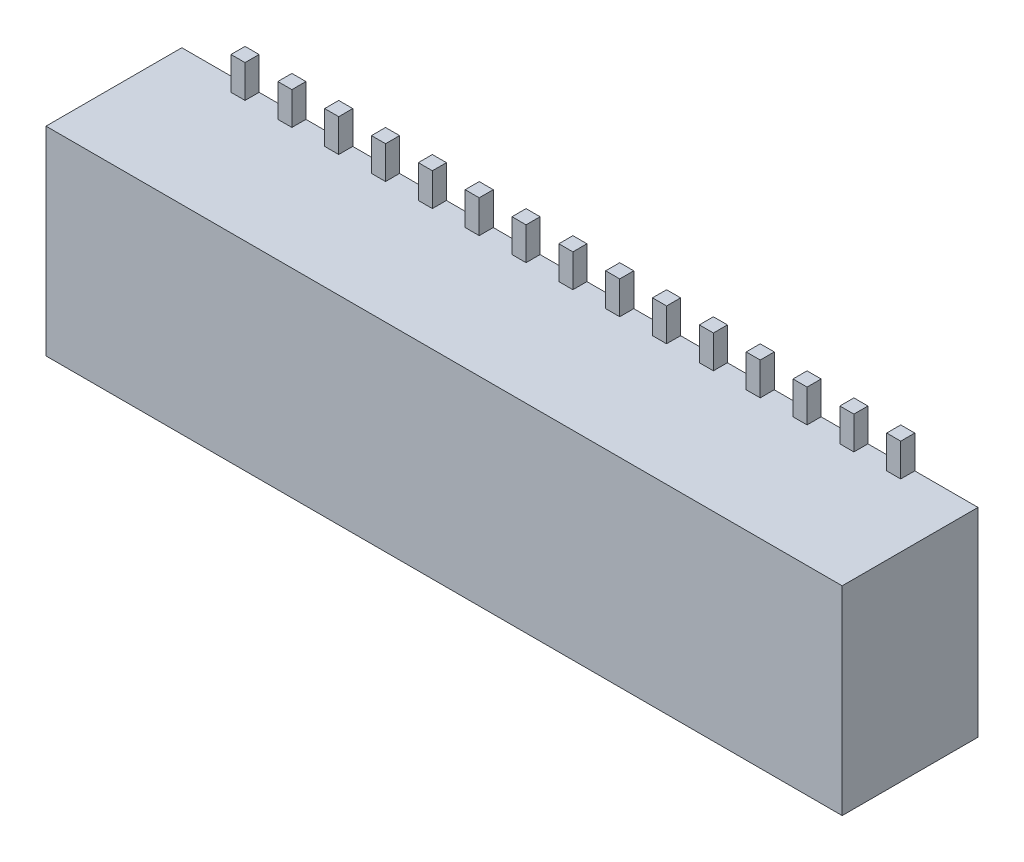
SolidWorks part; units mm, degrees
ref_plane "Front Plane" through (0, 0, 0) normal (0, 0, 1) x (1, 0, 0)
ref_plane "Top Plane" through (0, 0, 0) normal (0, 1, 0) x (1, 0, 0)
ref_plane "Right Plane" through (0, 0, 0) normal (1, 0, 0) x (0, 0, -1)
sketch "Sketch1" plane through (0, 0, 0) normal (0, 0, 1) x (1, 0, 0)
  line L1 (-8.5, 2.125) -> (8.5, 2.125)
  line L2 (-8.5, 2.125) -> (-8.5, -2.125)
  line L3 (-8.5, -2.125) -> (8.5, -2.125)
  line L4 (8.5, 2.125) -> (8.5, -2.125)
  line L5 (-8.5, 2.125) -> (8.5, -2.125) construction
  line L6 (-8.5, -2.125) -> (8.5, 2.125) construction
  point P0 (0, 0)
  dimension "D1" = 17
  dimension "D2" = 4.25
extrude "Boss-Extrude1" add sketch "Sketch1" along normal blind 2.9
sketch "Sketch2" plane through (0, -2.125, 0) normal (0, -1, 0) x (1, 0, 0)
  line L0 (-8.5, 0) -> (8.5, 0) construction
  line L1 (-7.7, 2.4) -> (7.7, 2.4)
  line L2 (-7.7, 2.4) -> (-7.7, 0.5)
  line L3 (-7.7, 0.5) -> (7.7, 0.5)
  line L4 (7.7, 2.4) -> (7.7, 0.5)
  line L5 (-8.5, 2.9) -> (8.5, 2.9) construction
  line L6 (-8.5, 2.9) -> (-8.5, 0) construction
  line L7 (8.5, 2.9) -> (8.5, 0) construction
  dimension "D1" = 0.5
  dimension "D2" = 0.5
  dimension "D3" = 0.8
  dimension "D4" = 0.8
extrude "Cut-Extrude1" cut sketch "Sketch2" against normal blind 2.9
sketch "Sketch3" plane through (0, 0.775, 0) normal (0, -1, 0) x (1, 0, 0)
  line L0 (-7.7, 1.45) -> (-7.15, 1.45) construction
  line L1 (-7.15, 1.75) -> (-6.85, 1.75)
  line L2 (-7.15, 1.75) -> (-7.15, 1.15)
  line L3 (-7.15, 1.15) -> (-6.85, 1.15)
  line L4 (-6.85, 1.75) -> (-6.85, 1.15)
  line L5 (-7.7, 2.4) -> (-7.7, 0.5) construction
  line L6 (-5.85, 1.75) -> (-5.85, 1.15)
  line L7 (-6.15, 1.15) -> (-5.85, 1.15)
  line L8 (-6.15, 1.75) -> (-6.15, 1.15)
  line L9 (-6.15, 1.75) -> (-5.85, 1.75)
  line L10 (-4.85, 1.75) -> (-4.85, 1.15)
  line L11 (-5.15, 1.15) -> (-4.85, 1.15)
  line L12 (-5.15, 1.75) -> (-5.15, 1.15)
  line L13 (-5.15, 1.75) -> (-4.85, 1.75)
  line L14 (-3.85, 1.75) -> (-3.85, 1.15)
  line L15 (-4.15, 1.15) -> (-3.85, 1.15)
  line L16 (-4.15, 1.75) -> (-4.15, 1.15)
  line L17 (-4.15, 1.75) -> (-3.85, 1.75)
  line L18 (-2.85, 1.75) -> (-2.85, 1.15)
  line L19 (-3.15, 1.15) -> (-2.85, 1.15)
  line L20 (-3.15, 1.75) -> (-3.15, 1.15)
  line L21 (-3.15, 1.75) -> (-2.85, 1.75)
  line L22 (-1.85, 1.75) -> (-1.85, 1.15)
  line L23 (-2.15, 1.15) -> (-1.85, 1.15)
  line L24 (-2.15, 1.75) -> (-2.15, 1.15)
  line L25 (-2.15, 1.75) -> (-1.85, 1.75)
  line L26 (-0.85, 1.75) -> (-0.85, 1.15)
  line L27 (-1.15, 1.15) -> (-0.85, 1.15)
  line L28 (-1.15, 1.75) -> (-1.15, 1.15)
  line L29 (-1.15, 1.75) -> (-0.85, 1.75)
  line L30 (0.15, 1.75) -> (0.15, 1.15)
  line L31 (-0.15, 1.15) -> (0.15, 1.15)
  line L32 (-0.15, 1.75) -> (-0.15, 1.15)
  line L33 (-0.15, 1.75) -> (0.15, 1.75)
  line L34 (1.15, 1.75) -> (1.15, 1.15)
  line L35 (0.85, 1.15) -> (1.15, 1.15)
  line L36 (0.85, 1.75) -> (0.85, 1.15)
  line L37 (0.85, 1.75) -> (1.15, 1.75)
  line L38 (2.15, 1.75) -> (2.15, 1.15)
  line L39 (1.85, 1.15) -> (2.15, 1.15)
  line L40 (1.85, 1.75) -> (1.85, 1.15)
  line L41 (1.85, 1.75) -> (2.15, 1.75)
  line L42 (3.15, 1.75) -> (3.15, 1.15)
  line L43 (2.85, 1.15) -> (3.15, 1.15)
  line L44 (2.85, 1.75) -> (2.85, 1.15)
  line L45 (2.85, 1.75) -> (3.15, 1.75)
  line L46 (4.15, 1.75) -> (4.15, 1.15)
  line L47 (3.85, 1.15) -> (4.15, 1.15)
  line L48 (3.85, 1.75) -> (3.85, 1.15)
  line L49 (3.85, 1.75) -> (4.15, 1.75)
  line L50 (5.15, 1.75) -> (5.15, 1.15)
  line L51 (4.85, 1.15) -> (5.15, 1.15)
  line L52 (4.85, 1.75) -> (4.85, 1.15)
  line L53 (4.85, 1.75) -> (5.15, 1.75)
  line L54 (6.15, 1.75) -> (6.15, 1.15)
  line L55 (5.85, 1.15) -> (6.15, 1.15)
  line L56 (5.85, 1.75) -> (5.85, 1.15)
  line L57 (5.85, 1.75) -> (6.15, 1.75)
  line L58 (7.15, 1.75) -> (7.15, 1.15)
  line L59 (6.85, 1.15) -> (7.15, 1.15)
  line L60 (6.85, 1.75) -> (6.85, 1.15)
  line L61 (6.85, 1.75) -> (7.15, 1.75)
  line L62 (0, 1.15) -> (0, 0) construction
  dimension "D1" = 0.3
  dimension "D2" = 0.6
  dimension "D3" = 15
  dimension "D4" = 1
extrude "Boss-Extrude2" add sketch "Sketch3" along normal blind 2.5
sketch "Sketch4" plane through (0, 0, 0) normal (0, 0, -1) x (-1, 0, 0)
  line L0 (-6.85, -1.725) -> (-6.85, 0.775) construction
  line L1 (-7.15, 2.025) -> (-6.85, 2.025)
  line L2 (-7.15, 2.025) -> (-7.15, 2.825)
  line L3 (-7.15, 2.825) -> (-6.85, 2.825)
  line L4 (-6.85, 2.025) -> (-6.85, 2.825)
  line L5 (-7.15, -1.725) -> (-7.15, 0.775) construction
  line L6 (-8.5, 2.125) -> (8.5, 2.125) construction
  line L7 (-5.85, 2.025) -> (-5.85, 2.825)
  line L8 (-6.15, 2.025) -> (-5.85, 2.025)
  line L9 (-6.15, 2.025) -> (-6.15, 2.825)
  line L10 (-6.15, 2.825) -> (-5.85, 2.825)
  line L11 (-4.85, 2.025) -> (-4.85, 2.825)
  line L12 (-5.15, 2.025) -> (-4.85, 2.025)
  line L13 (-5.15, 2.025) -> (-5.15, 2.825)
  line L14 (-5.15, 2.825) -> (-4.85, 2.825)
  line L15 (-3.85, 2.025) -> (-3.85, 2.825)
  line L16 (-4.15, 2.025) -> (-3.85, 2.025)
  line L17 (-4.15, 2.025) -> (-4.15, 2.825)
  line L18 (-4.15, 2.825) -> (-3.85, 2.825)
  line L19 (-2.85, 2.025) -> (-2.85, 2.825)
  line L20 (-3.15, 2.025) -> (-2.85, 2.025)
  line L21 (-3.15, 2.025) -> (-3.15, 2.825)
  line L22 (-3.15, 2.825) -> (-2.85, 2.825)
  line L23 (-1.85, 2.025) -> (-1.85, 2.825)
  line L24 (-2.15, 2.025) -> (-1.85, 2.025)
  line L25 (-2.15, 2.025) -> (-2.15, 2.825)
  line L26 (-2.15, 2.825) -> (-1.85, 2.825)
  line L27 (-0.85, 2.025) -> (-0.85, 2.825)
  line L28 (-1.15, 2.025) -> (-0.85, 2.025)
  line L29 (-1.15, 2.025) -> (-1.15, 2.825)
  line L30 (-1.15, 2.825) -> (-0.85, 2.825)
  line L31 (0.15, 2.025) -> (0.15, 2.825)
  line L32 (-0.15, 2.025) -> (0.15, 2.025)
  line L33 (-0.15, 2.025) -> (-0.15, 2.825)
  line L34 (-0.15, 2.825) -> (0.15, 2.825)
  line L35 (1.15, 2.025) -> (1.15, 2.825)
  line L36 (0.85, 2.025) -> (1.15, 2.025)
  line L37 (0.85, 2.025) -> (0.85, 2.825)
  line L38 (0.85, 2.825) -> (1.15, 2.825)
  line L39 (2.15, 2.025) -> (2.15, 2.825)
  line L40 (1.85, 2.025) -> (2.15, 2.025)
  line L41 (1.85, 2.025) -> (1.85, 2.825)
  line L42 (1.85, 2.825) -> (2.15, 2.825)
  line L43 (3.15, 2.025) -> (3.15, 2.825)
  line L44 (2.85, 2.025) -> (3.15, 2.025)
  line L45 (2.85, 2.025) -> (2.85, 2.825)
  line L46 (2.85, 2.825) -> (3.15, 2.825)
  line L47 (4.15, 2.025) -> (4.15, 2.825)
  line L48 (3.85, 2.025) -> (4.15, 2.025)
  line L49 (3.85, 2.025) -> (3.85, 2.825)
  line L50 (3.85, 2.825) -> (4.15, 2.825)
  line L51 (5.15, 2.025) -> (5.15, 2.825)
  line L52 (4.85, 2.025) -> (5.15, 2.025)
  line L53 (4.85, 2.025) -> (4.85, 2.825)
  line L54 (4.85, 2.825) -> (5.15, 2.825)
  line L55 (6.15, 2.025) -> (6.15, 2.825)
  line L56 (5.85, 2.025) -> (6.15, 2.025)
  line L57 (5.85, 2.025) -> (5.85, 2.825)
  line L58 (5.85, 2.825) -> (6.15, 2.825)
  line L59 (7.15, 2.025) -> (7.15, 2.825)
  line L60 (6.85, 2.025) -> (7.15, 2.025)
  line L61 (6.85, 2.025) -> (6.85, 2.825)
  line L62 (6.85, 2.825) -> (7.15, 2.825)
  point P11 (5.2803, 2.825)
  dimension "D1" = 0.7
  dimension "D2" = 0.1
  dimension "D4" = 1
  dimension "D3" = 15
extrude "Boss-Extrude3" add sketch "Sketch4" against normal blind 0.3
